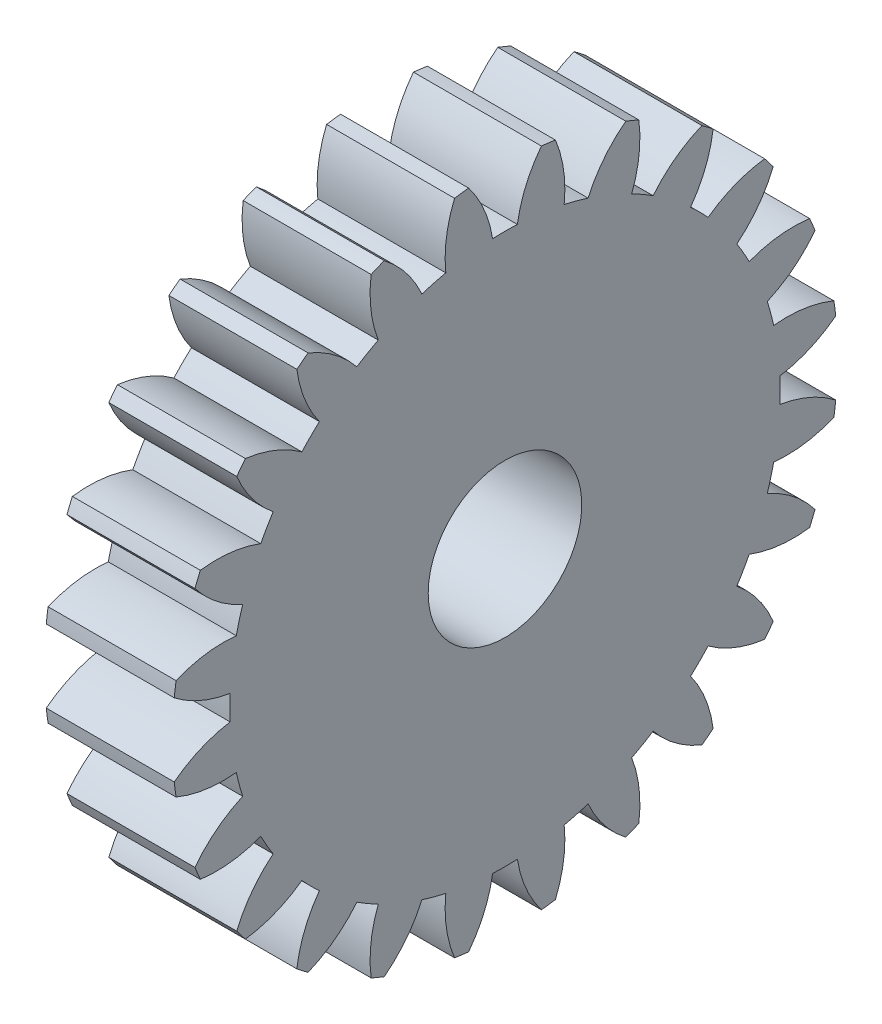
SolidWorks part; units mm, degrees
ref_plane "Plane1" through (0, 0, 0) normal (0, 0, 1) x (1, 0, 0)
ref_plane "Plane2" through (0, 0, 0) normal (0, 1, 0) x (1, 0, 0)
ref_plane "Plane3" through (0, 0, 0) normal (1, 0, 0) x (0, 0, -1)
sketch "HoldingSke" plane through (0, 0, 0) normal (0, 1, 0) x (1, 0, 0)
  line L0 (0, 0) -> (0.9135, -0.4067)
  line L1 (-15, 0) -> (100, 0) construction
  line L2 (0, 0) -> (-2.1039, 2.3779)
  line L3 (0, 0) -> (-11.863, 4.5341)
  line L4 (0, 0) -> (7.8894, 3.5126)
  line L5 (0, 0) -> (-46.8476, -17.4728)
  line L6 (0, 0) -> (-4.1448, -2.7965)
  line L7 (-2.1039, 2.3779) -> (8.6586, 51.2059)
  line L8 (-76.2, 54.61) -> (-75.2, 54.61)
  line L9 (-71.009, 38.7566) -> (-53.1078, 45.2721)
  line L10 (-76.2, 71.12) -> (104.1128, 71.12)
  line L11 (0, 0) -> (-5, 0)
  line L12 (-76.2, 101.6) -> (-76.162, 101.6)
  line L13 (24.9733, 27.94) -> (52.9518, 28.4284)
  line L14 (24.9733, 27.94) -> (24.9743, 27.94)
  line L15 (24.9733, 27.94) -> (100.4006, 29.5858)
  line L16 (-63.627, -1) -> (-12.827, -1)
  circle A0 centre (0, 0) radius 3
  circle A1 centre (0, 0) radius 10.749
  circle A2 centre (0, 0) radius 37.5
  circle A3 centre (0, 0) radius 3
  dimension "MHD" = 21.498
  dimension "Hub_dia" = 75
  dimension "Bore" = 6
  dimension "MBD" = 6
  dimension "Num_teeth" = 24
  dimension "Pitch" = 1
  dimension "Overall_len" = 50
  dimension "Show_teeth" = 24
  dimension "Thickness" = 5
  dimension "OAL" = 50.0001
  dimension "T_dim" = 1
  dimension "Ap" = 20
  dimension "H" = 19.05
  dimension "Pitch_radius" = 180.3128
  dimension "Width" = 5
  dimension "Backlash" = 0.038
  dimension "Addendum_fac" = 1
  dimension "Dedendum_fac" = 1.25
  dimension "Clearance_fac" = 0.25
  dimension "Dedendum_add" = 0.001
  dimension "Module" = 1
sketch "BasProSke" plane through (0, 0, 0) normal (0, 1, 0) x (1, 0, 0)
  line L0 (-10, 0) -> (60, 0) construction
  line L1 (0, 0) -> (0, 13)
  line L2 (0, 0) -> (5, 0)
  line L3 (5, 0) -> (5, 13)
  line L4 (5, 13) -> (0, 13)
  dimension "Thickness" = 5
  dimension "Diameter" = 26
revolve "Base-Revolve" add sketch "BasProSke" angle 360 about L0
sketch "TooCutSke" plane through (0, 0, 0) normal (1, 0, 0) x (0, 0, -1)
  line L1 (0, 0) -> (0, 107) construction
  line L2 (0, 0) -> (-0.8513, 11.9698) construction
  line L3 (0, 0) -> (-3.127, 23.752) construction
  line L4 (-0.8513, 11.9698) -> (-1.5635, 11.876) construction
  arc A0 (0.4834, 10.7381) -> (-0.4834, 10.7381) centre (0, 0) ccw
  arc A1 (1.4409, 12.9455) -> (-1.4409, 12.9455) centre (0, 0) ccw
  circle A2 centre (0, 0) radius 12 construction
  circle A3 centre (0, 0) radius 11.2763 construction
  arc A4 (-0.4834, 10.7381) -> (-1.4409, 12.9455) centre (-5.2252, 9.9926) ccw
  arc A5 (1.4409, 12.9455) -> (0.4834, 10.7381) centre (5.2252, 9.9926) ccw
  dimension "Root_dia" = 21.498
  dimension "Overcut_dia" = 26.0508
  dimension "Pitch_dia" = 24
  dimension "Base_dia" = 22.5526
  dimension "Flank_rad" = 4.8
  dimension "Half_ang" = 7.5
  dimension "Half_CT" = 0.7183
extrude "ToothCut" cut sketch "TooCutSke" along normal through all
fillet "Breaks" [suppressed] radius 0.02
fillet "RootFillets" [suppressed] radius 0.251
pattern_circular "TeethCuts" count 24 every 15 about axis through (-10, 0, 0) along (1, 0, 0) of "ToothCut", "RootFillets", "Breaks"
sketch "HubNeaOneSke" plane through (0, 0, 0) normal (-1, 0, 0) x (0, 0, 1)
  circle A0 centre (0, 0) radius 10.749
  dimension "Diameter" = 21.498
extrude "HubNearOne" [suppressed] add sketch "HubNeaOneSke" along normal blind 45.0001
sketch "HubNeaBotSke" plane through (0, 0, 0) normal (-1, 0, 0) x (0, 0, 1)
  circle A0 centre (0, 0) radius 10.749
  dimension "Diameter" = 21.498
extrude "HubNearBoth" [suppressed] add sketch "HubNeaBotSke" along normal blind 22.5
ref_plane "FarPln" through (5, 0, 0) normal (1, 0, 0) x (0, 0, -1)
sketch "HubFarSke" plane through (5, 0, 0) normal (1, 0, 0) x (0, 0, -1)
  circle A0 centre (0, 0) radius 10.749
  dimension "Diameter" = 21.498
extrude "HubFar" [suppressed] add sketch "HubFarSke" along normal blind 22.5
sketch "BorSke" plane through (0, 0, 0) normal (1, 0, 0) x (0, 0, -1)
  circle A0 centre (0, 0) radius 3
  dimension "Diameter" = 6
extrude "Bore" cut sketch "BorSke" along normal mid plane 100.0001
sketch "KeySke" plane through (0, 0, 0) normal (1, 0, 0) x (0, 0, -1)
  line L0 (-1, 0) -> (-1, 4)
  line L1 (-1, 4) -> (1, 4)
  line L2 (1, 4) -> (1, 0)
  line L3 (0, 0) -> (0, 34) construction
  line L4 (-1, 0) -> (1, 0)
  dimension "Offset" = 4
  dimension "Width" = 2
extrude "Keyway" [suppressed] cut sketch "KeySke" along normal mid plane 100.0001
pattern_circular "Keyway2" [suppressed] count 2 every 90 about axis through (-10, 0, 0) along (1, 0, 0)
equation "' \"Module@HoldingSke\" = 6.35"
equation "' \"Num_teeth@HoldingSke\" = 12"
equation "' \"Ap@HoldingSke\" =  20"
equation "' \"Ap@HoldingSke\" = 20"
equation "' \"Width@HoldingSke\" = 0.5 * 25.4"
equation "' \"Hub_dia@HoldingSke\"= 1 * 25.4"
equation "' \"Hub_dia@HoldingSke\" = 1 * 25.4"
equation "' \"Overall_len@HoldingSke\" = 1.0 * 25.4"
equation "' \"Bore@HoldingSke\" = 0.75 * 25.4"
equation "' \"T_dim@HoldingSke\" = 0.1 * 25.4"
equation "' \"Width@KeySke\" = 0.25 * 25.4"
equation "' \"Show_teeth@HoldingSke\" = 13"
equation "' \"Backlash@HoldingSke\" = 0.009 * 25.4"
equation "' \"Addendum_fac@HoldingSke\" = 1.0"
equation "' \"Dedendum_fac@HoldingSke\" = 1.25"
equation "' \"Dedendum_add@HoldingSke\" = 0.00005 * 25.4"
equation "' \"Clearance_fac@HoldingSke\" = 0.25"
equation "\"Pitch@HoldingSke\" = 1 / \"Module@HoldingSke\""
equation "\"Overcut_dia@TooCutSke\" = (\"Num_teeth@HoldingSke\" + 2 * \"Addendum_fac@HoldingSke\") / \"Pitch@HoldingSke\" + 0.002 * 25.4"
equation "\"Pitch_dia@TooCutSke\" = \"Num_teeth@HoldingSke\" / \"Pitch@HoldingSke\""
equation "\"Base_dia@TooCutSke\" = \"Num_teeth@HoldingSke\" / \"Pitch@HoldingSke\" * cos((\"Ap@HoldingSke\"  * 3.14159265 / 180))"
equation "\"Root_dia@TooCutSke\" = (\"Num_teeth@HoldingSke\" + 2) / \"Pitch@HoldingSke\" - 2 * (\"Addendum_fac@HoldingSke\" + \"Dedendum_fac@HoldingSke\") / \"Pitch@HoldingSke\" - \"Dedendum_add@HoldingSke\" * 2"
equation "\"Half_ang@TooCutSke\" = 180 / \"Num_teeth@HoldingSke\""
equation "\"Half_CT@TooCutSke\" = \"Num_teeth@HoldingSke\" / \"Pitch@HoldingSke\" * sin((3.14159265 / 2 / \"Num_teeth@HoldingSke\")) / 2 - 7 * \"Backlash@HoldingSke\" / 4"
equation "\"Flank_rad@TooCutSke\" = \"Num_teeth@HoldingSke\" / \"Pitch@HoldingSke\" / 5"
equation "\"Radius@RootFillets\" = \"Clearance_fac@HoldingSke\" / \"Pitch@HoldingSke\" + \"Dedendum_add@HoldingSke\""
equation "\"Break_rad@Breaks\" = 0.02 / \"Pitch@HoldingSke\""
equation "\"Thickness@HoldingSke\" = \"Width@HoldingSke\""
equation "\"OAL@HoldingSke\" = \"Thickness@HoldingSke\""
equation "\"MHD@HoldingSke\" = (\"Num_teeth@HoldingSke\" + 2) / \"Pitch@HoldingSke\" - 2 * (\"Addendum_fac@HoldingSke\" + \"Dedendum_fac@HoldingSke\")  / \"Pitch@HoldingSke\" - \"Dedendum_add@HoldingSke\" * 2"
equation "\"MBD@HoldingSke\" = (\"Num_teeth@HoldingSke\" + 2) / \"Pitch@HoldingSke\" - 2 * (\"Addendum_fac@HoldingSke\" + \"Dedendum_fac@HoldingSke\")  / \"Pitch@HoldingSke\" - \"Dedendum_add@HoldingSke\" * 2 - 0.002 * 25.4"
equation "\"MHD@HoldingSke\" = ((sgn( \"MHD@HoldingSke\" - \"Hub_dia@HoldingSke\" )-1)*( \"MHD@HoldingSke\" - \"Hub_dia@HoldingSke\" ))/-2+ \"Hub_dia@HoldingSke\""
equation "\"MBD@HoldingSke\" = ((sgn( \"MBD@HoldingSke\" - \"Bore@HoldingSke\" )-1)*( \"MBD@HoldingSke\" - \"Bore@HoldingSke\" ))/-2+ \"Bore@HoldingSke\""
equation "\"OAL@HoldingSke\" = ((sgn( \"OAL@HoldingSke\" - \"Overall_len@HoldingSke\" )+1)*( \"OAL@HoldingSke\" - \"Overall_len@HoldingSke\" ))/2 + \"Overall_len@HoldingSke\" + 0.000002 * 25.4"
equation "\"Num_teeth@TeethCuts\" = int( \"Show_teeth@HoldingSke\" ) + 1"
equation "\"Num_teeth@TeethCuts\" = ((sgn( \"Num_teeth@TeethCuts\" - \"Num_teeth@HoldingSke\" )-1)*( \"Num_teeth@TeethCuts\" - \"Num_teeth@HoldingSke\" ))/-2+ \"Num_teeth@HoldingSke\""
equation "\"Num_teeth@TeethCuts\" = ((sgn( \"Num_teeth@TeethCuts\" - 2.0)+1)*( \"Num_teeth@TeethCuts\" - 2.0))/2 +2.0"
equation "\"Angle@TeethCuts\" = 360.0 / \"Num_teeth@HoldingSke\""
equation "\"Diameter@BasProSke\" = (\"Num_teeth@HoldingSke\" + 2 * \"Addendum_fac@HoldingSke\") / \"Pitch@HoldingSke\""
equation "\"Thickness@BasProSke\"  = \"Thickness@HoldingSke\""
equation "' \"Fillet_rad@BasProSke\" =  \"Thickness@HoldingSke\" * 0.05"
equation "' \"Fillet_rad@BasProSke\" = \"Thickness@HoldingSke\" * 0.05"
equation "\"MHD@HoldingSke\" = ((sgn( \"MHD@HoldingSke\" - \"Root_dia@TooCutSke\" )-1)*( \"MHD@HoldingSke\" - \"Root_dia@TooCutSke\" ))/-2+ \"Root_dia@TooCutSke\""
equation "\"Diameter@HubNeaOneSke\" = \"MHD@HoldingSke\""
equation "\"Length@HubNearOne\" = \"OAL@HoldingSke\" - \"Thickness@BasProSke\""
equation "\"Diameter@HubNeaBotSke\" = \"MHD@HoldingSke\""
equation "\"Length@HubNearBoth\" = ( \"OAL@HoldingSke\" - \"Thickness@BasProSke\" ) / 2.0"
equation "\"Thickness@FarPln\" = \"Thickness@BasProSke\""
equation "\"Diameter@HubFarSke\" = \"MHD@HoldingSke\""
equation "\"Length@HubFar\" = ( \"OAL@HoldingSke\" - \"Thickness@BasProSke\" ) / 2.0"
equation "\"Diameter@BorSke\" = \"MBD@HoldingSke\""
equation "\"D1@Bore\" = \"OAL@HoldingSke\" * 2.0"
equation "\"D1@Keyway\" = \"OAL@HoldingSke\" * 2.0"
equation "\"Offset@KeySke\" = \"T_dim@HoldingSke\" + \"MBD@HoldingSke\" / 2.0"
